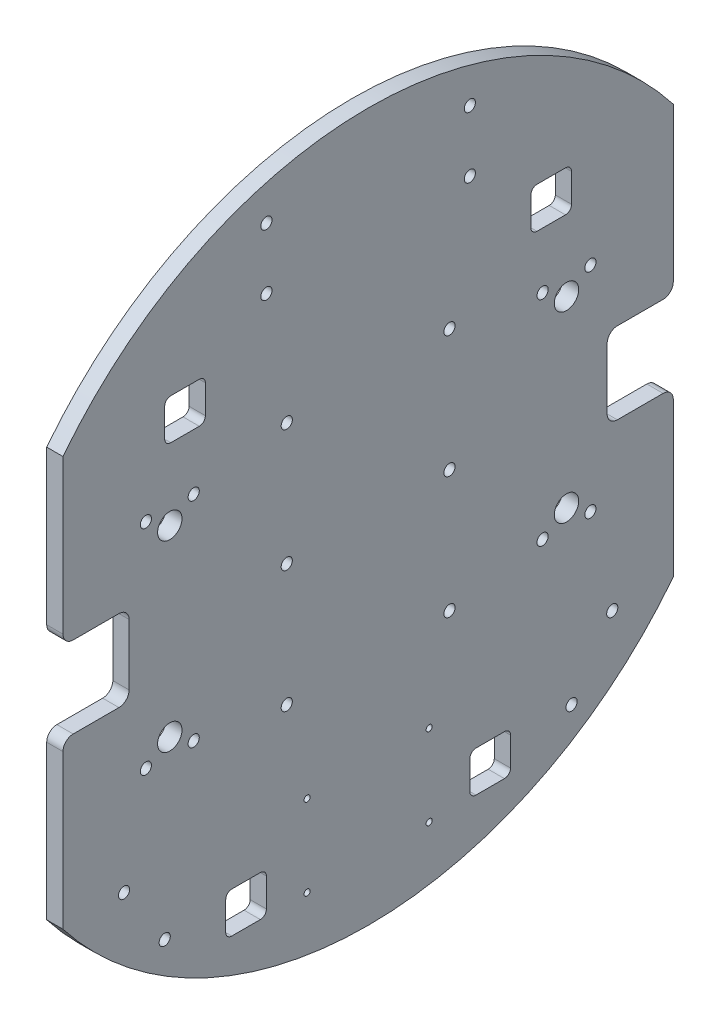
SolidWorks part; units mm, degrees
ref_plane "前视基准面" through (0, 0, 0) normal (0, 0, 1) x (1, 0, 0)
ref_plane "上视基准面" through (0, 0, 0) normal (0, 1, 0) x (1, 0, 0)
ref_plane "右视基准面" through (0, 0, 0) normal (1, 0, 0) x (0, 0, -1)
other "Configuration Table"
sketch "草图1" plane through (0, 0, 0) normal (1, 0, 0) x (0, 0, -1)
  line L0 (0, 0) -> (50000, 0) construction
  line L2 (-150, 100.619) -> (-150, -100.619)
  line L4 (150, 100.619) -> (150, -100.619)
  arc A0 (150, 100.619) -> (-150, 100.619) centre (0, -16) ccw
  arc A1 (150, -100.619) -> (-150, -100.619) centre (0, 16) cw
  dimension "D1" = 150
  dimension "D4" = 190
  dimension "D2" = 16
  dimension "D5" = 300
extrude "凸台-拉伸1" add sketch "草图1" along normal blind 8
sketch "草图2" plane through (8, 0, 0) normal (1, 0, 0) x (0, 0, -1)
  line L0 (97.5, 45) -> (97.5, -45) construction
  line L1 (0, 0) -> (0, 50000) construction
  line L2 (85.75, 52.5) -> (109.25, 52.5) construction
  line L3 (85.75, 52.5) -> (85.75, -52.5) construction
  line L4 (85.75, -52.5) -> (109.25, -52.5) construction
  line L5 (109.25, 52.5) -> (109.25, -52.5) construction
  line L6 (-109.25, 52.5) -> (-109.25, -52.5) construction
  line L7 (-85.75, -52.5) -> (-109.25, -52.5) construction
  line L8 (-85.75, 52.5) -> (-85.75, -52.5) construction
  line L9 (-85.75, 52.5) -> (-109.25, 52.5) construction
  line L10 (-97.5, 45) -> (-97.5, -45) construction
  circle A0 centre (97.5, 45) radius 6
  circle A1 centre (97.5, -45) radius 6
  circle A2 centre (85.75, 52.5) radius 2.75
  circle A3 centre (109.25, 52.5) radius 2.75
  circle A4 centre (85.75, -52.5) radius 2.75
  circle A5 centre (109.25, -52.5) radius 2.75
  circle A6 centre (-109.25, -52.5) radius 2.75
  circle A7 centre (-85.75, -52.5) radius 2.75
  circle A8 centre (-109.25, 52.5) radius 2.75
  circle A9 centre (-85.75, 52.5) radius 2.75
  circle A10 centre (-97.5, -45) radius 6
  circle A11 centre (-97.5, 45) radius 6
  point P9 (97.5, 0)
  dimension "D4" = 12
  dimension "D5" = 12
  dimension "D10" = 5.5
  dimension "D1" = 90
  dimension "D2" = 97.5
  dimension "D3" = 45
  dimension "D6" = 23.5
  dimension "D7" = 11.75
  dimension "D8" = 105
  dimension "D9" = 52.5
extrude "切除-拉伸1" cut sketch "草图2" against normal blind 8
sketch "草图3" plane through (8, 0, 0) normal (1, 0, 0) x (0, 0, -1)
  line L1 (-40, 60) -> (40, 60) construction
  line L2 (-40, 60) -> (-40, -60) construction
  line L3 (-40, -60) -> (40, -60) construction
  line L4 (40, 60) -> (40, -60) construction
  circle A0 centre (-40, 60) radius 2.75
  circle A2 centre (40, 60) radius 2.75
  circle A3 centre (40, -60) radius 2.75
  circle A5 centre (-40, -60) radius 2.75
  circle A6 centre (40, 0) radius 2.75
  circle A7 centre (-40, 0) radius 2.75
  dimension "D5" = 5.5
  dimension "D6" = 5.5
  dimension "D1" = 120
  dimension "D2" = 80
  dimension "D3" = 60
  dimension "D4" = 40
extrude "切除-拉伸2" cut sketch "草图3" against normal blind 10
sketch "草图4" plane through (8, 0, 0) normal (1, 0, 0) x (0, 0, -1)
  line L0 (0, 0) -> (0, 50000) construction
  line L1 (117.5, 20) -> (150, 20)
  line L2 (117.5, 20) -> (117.5, -20)
  line L3 (117.5, -20) -> (150, -20)
  line L4 (150, 20) -> (150, -20)
  line L5 (150, -100.619) -> (150, 100.619) construction
  line L6 (-150, 20) -> (-150, -20)
  line L7 (-117.5, -20) -> (-150, -20)
  line L8 (-117.5, 20) -> (-117.5, -20)
  line L9 (-117.5, 20) -> (-150, 20)
  dimension "D1" = 40
  dimension "D2" = 20
  dimension "D3" = 117.5
extrude "切除-拉伸3" cut sketch "草图4" against normal blind 10
fillet "圆角1" radius 5 8 edges at (4, -20, 117.5) (4, -20, 150) (4, 20, 150) (4, 20, 117.5) (4, -20, -150) (4, 20, -150) (4, -20, -117.5) (4, 20, -117.5)
sketch "草图5" plane through (8, 0, 0) normal (1, 0, 0) x (0, 0, -1)
  line L1 (-50, 150) -> (50, 150) construction
  line L2 (-50, 150) -> (-50, 120) construction
  line L3 (-50, 120) -> (50, 120) construction
  line L4 (50, 150) -> (50, 120) construction
  circle A0 centre (50, 150) radius 2.75
  circle A1 centre (-50, 150) radius 2.75
  circle A2 centre (-50, 120) radius 2.75
  circle A3 centre (50, 120) radius 2.75
  dimension "D5" = 5.5
  dimension "D1" = 100
  dimension "D2" = 30
  dimension "D3" = 120
  dimension "D4" = 50
extrude "切除-拉伸4" cut sketch "草图5" against normal through all
sketch "草图6" plane through (8, 0, 0) normal (1, 0, 0) x (0, 0, -1)
  line L0 (0, 0) -> (0, 50000) construction
  line L1 (-100, 100) -> (-80, 100)
  line L2 (-100, 100) -> (-100, 80)
  line L3 (-100, 80) -> (-80, 80)
  line L4 (-80, 100) -> (-80, 80)
  line L5 (80, 100) -> (80, 80)
  line L6 (100, 80) -> (80, 80)
  line L7 (100, 100) -> (100, 80)
  line L8 (100, 100) -> (80, 100)
  dimension "D1" = 20
  dimension "D2" = 80
  dimension "D3" = 80
extrude "切除-拉伸5" cut sketch "草图6" against normal through all
fillet "圆角2" radius 3 8 edges at (4, 100, 80) (4, 100, 100) (4, 80, 80) (4, 80, 100) (4, 80, -80) (4, 80, -100) (4, 100, -100) (4, 100, -80)
sketch "草图7" plane through (8, 0, 0) normal (1, 0, 0) x (0, 0, -1)
  line L0 (0, 0) -> (0, -50000) construction
  line L1 (-30, -105) -> (30, -105) construction
  line L2 (-30, -105) -> (-30, -145) construction
  line L3 (-30, -145) -> (30, -145) construction
  line L4 (30, -105) -> (30, -145) construction
  line L13 (-120, -100) -> (-120, -130) construction
  line L14 (100, -100) -> (120, -100) construction
  line L15 (100, -100) -> (100, -130) construction
  line L16 (100, -130) -> (120, -130) construction
  line L17 (120, -100) -> (120, -130) construction
  line L18 (-100, -130) -> (-120, -130) construction
  line L19 (-100, -100) -> (-100, -130) construction
  line L20 (-100, -100) -> (-120, -100) construction
  circle A0 centre (-30, -105) radius 1.5
  circle A1 centre (-30, -145) radius 1.5
  circle A2 centre (30, -145) radius 1.5
  circle A3 centre (30, -105) radius 1.5
  circle A12 centre (120, -100) radius 2.75
  circle A13 centre (100, -130) radius 2.75
  circle A14 centre (-100, -130) radius 2.75
  circle A15 centre (-120, -100) radius 2.75
  dimension "D9" = 100
  dimension "D1" = 3
  dimension "D2" = 5.5
  dimension "D3" = 20
  dimension "D4" = 30
  dimension "D5" = 60
  dimension "D6" = 40
  dimension "D7" = 105
  dimension "D8" = 30
  dimension "D10" = 100
extrude "切除-拉伸6" cut sketch "草图7" against normal through all
sketch "草图8" plane through (8, 0, 0) normal (1, 0, 0) x (0, 0, -1)
  line L0 (0, 0) -> (0, -50000) construction
  line L1 (50, -125) -> (70, -125)
  line L2 (50, -125) -> (50, -145)
  line L3 (50, -145) -> (70, -145)
  line L4 (70, -125) -> (70, -145)
  line L5 (-70, -125) -> (-70, -145)
  line L6 (-50, -145) -> (-70, -145)
  line L7 (-50, -125) -> (-50, -145)
  line L8 (-50, -125) -> (-70, -125)
  dimension "D1" = 20
  dimension "D2" = 50
  dimension "D3" = 125
extrude "切除-拉伸7" cut sketch "草图8" against normal through all
fillet "圆角3" radius 3 8 edges at (4, -145, 70) (4, -125, 70) (4, -125, 50) (4, -145, 50) (4, -145, -70) (4, -145, -50) (4, -125, -50) (4, -125, -70)
